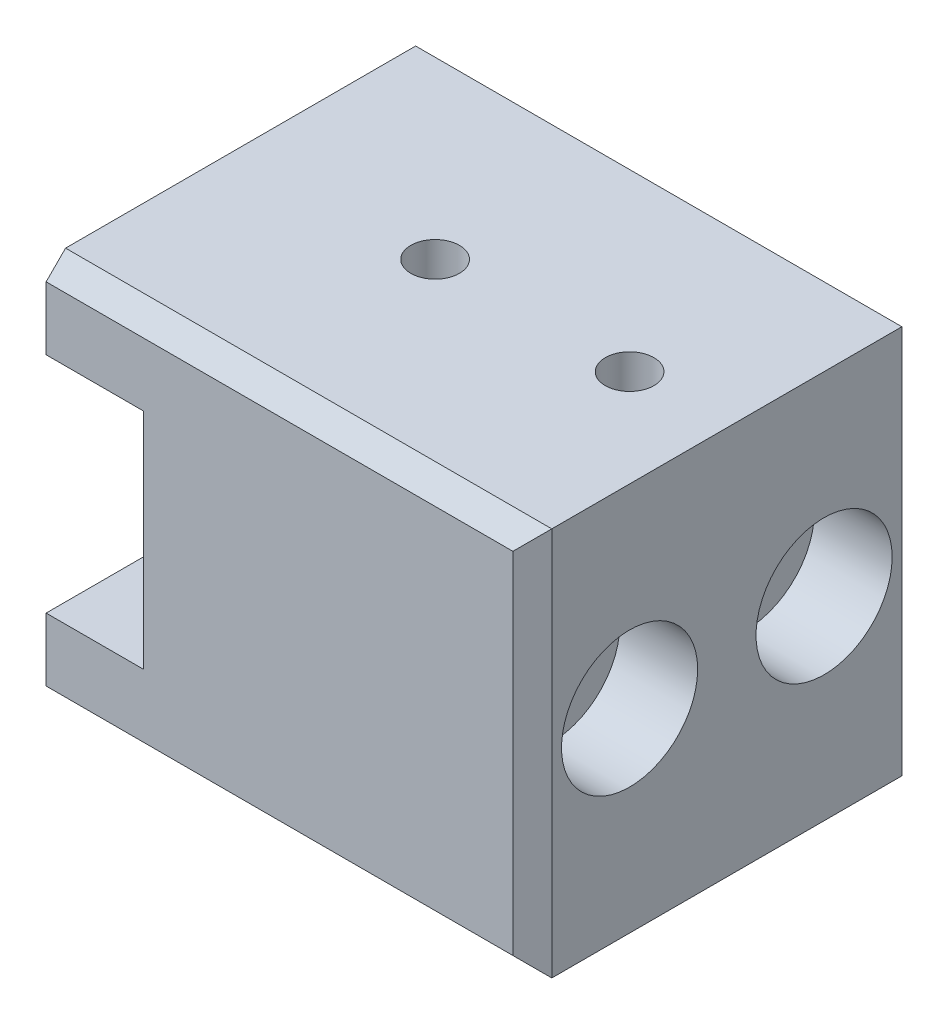
SolidWorks part; units mm, degrees
ref_plane "Front" through (0, 0, 0) normal (0, 0, 1) x (1, 0, 0)
ref_plane "Top" through (0, 0, 0) normal (0, 1, 0) x (1, 0, 0)
ref_plane "Right" through (0, 0, 0) normal (1, 0, 0) x (0, 0, -1)
sketch "草图1" plane through (0, 0, 0) normal (1, 0, 0) x (0, 0, -1)
  line L1 (10, -10) -> (-10, -10)
  line L2 (10, -10) -> (10, 10)
  line L3 (10, 10) -> (-10, 10)
  line L4 (-10, -10) -> (-10, 10)
  line L5 (10, -10) -> (-10, 10) construction
  line L6 (10, 10) -> (-10, -10) construction
  point P0 (0, 0)
  dimension "D1" = 20
  dimension "D2" = 20
extrude "凸台-拉伸1" add sketch "草图1" along normal blind 25
sketch "草图2" plane through (0, 0, 0) normal (-1, 0, 0) x (0, 0, 1)
  line L0 (-10, 0) -> (10, 0) construction
  line L1 (-10, -10) -> (-10, 10) construction
  line L2 (10, 10) -> (10, -10) construction
  line L4 (10, -5.75) -> (-10, -5.75)
  line L5 (10, -5.75) -> (10, 5.75)
  line L6 (10, 5.75) -> (-10, 5.75)
  line L7 (-10, -5.75) -> (-10, 5.75)
  line L8 (10, -5.75) -> (-10, 5.75) construction
  line L9 (10, 5.75) -> (-10, -5.75) construction
  point P6 (0, 0)
  point P11 (-6.2779, 6.3739)
  dimension "D1" = 11.5
extrude "切除-拉伸1" cut sketch "草图2" against normal blind 5
sketch "草图3" plane through (5, 0, 0) normal (-1, 0, 0) x (0, 0, 1)
  line L0 (-10, 0) -> (10, 0) construction
  line L1 (-10, 5.75) -> (-10, -5.75) construction
  line L2 (10, -5.75) -> (10, 5.75) construction
  line L3 (0, 5.75) -> (0, -5.75) construction
  line L4 (10, 5.75) -> (-10, 5.75) construction
  line L5 (-10, -5.75) -> (10, -5.75) construction
  circle A0 centre (-5, 0) radius 1.25
  circle A1 centre (5, 0) radius 1.25
  point P16 (0, 0)
  dimension "D1" = 2.5
  dimension "D2" = 2.5
  dimension "D3" = 10
extrude "切除-拉伸2" cut sketch "草图3" against normal through all
sketch "草图4" plane through (0, 10, 0) normal (0, 1, 0) x (1, 0, 0)
  line L0 (25, 0) -> (0, 0) construction
  line L1 (25, 10) -> (25, -10) construction
  line L2 (0, 10) -> (0, -10) construction
  circle A0 centre (20, 0) radius 1.25
  circle A1 centre (10, 0) radius 1.25
  dimension "D1" = 2.5
  dimension "D2" = 2.5
  dimension "D3" = 10
  dimension "D4" = 5
extrude "切除-拉伸3" cut sketch "草图4" against normal through all
chamfer "倒角1" distance 1 angle 45 8 edges at (12.5, -10, -10) (25, 10, 0) (12.5, 10, -10) (25, 0, -10) (25, -10, 0) (12.5, -10, 10) (25, 0, 10) (12.5, 10, 10)
sketch "草图6" plane through (25, 0, 0) normal (1, 0, 0) x (0, 0, -1)
  circle A0 centre (-5, 0) radius 3.5
  circle A1 centre (5, 0) radius 3.5
  circle A2 centre (5, 0) radius 1.25 construction
  circle A3 centre (-5, 0) radius 1.25 construction
  dimension "D1" = 7
  dimension "D2" = 7
extrude "切除-拉伸4" cut sketch "草图6" against normal blind 4
